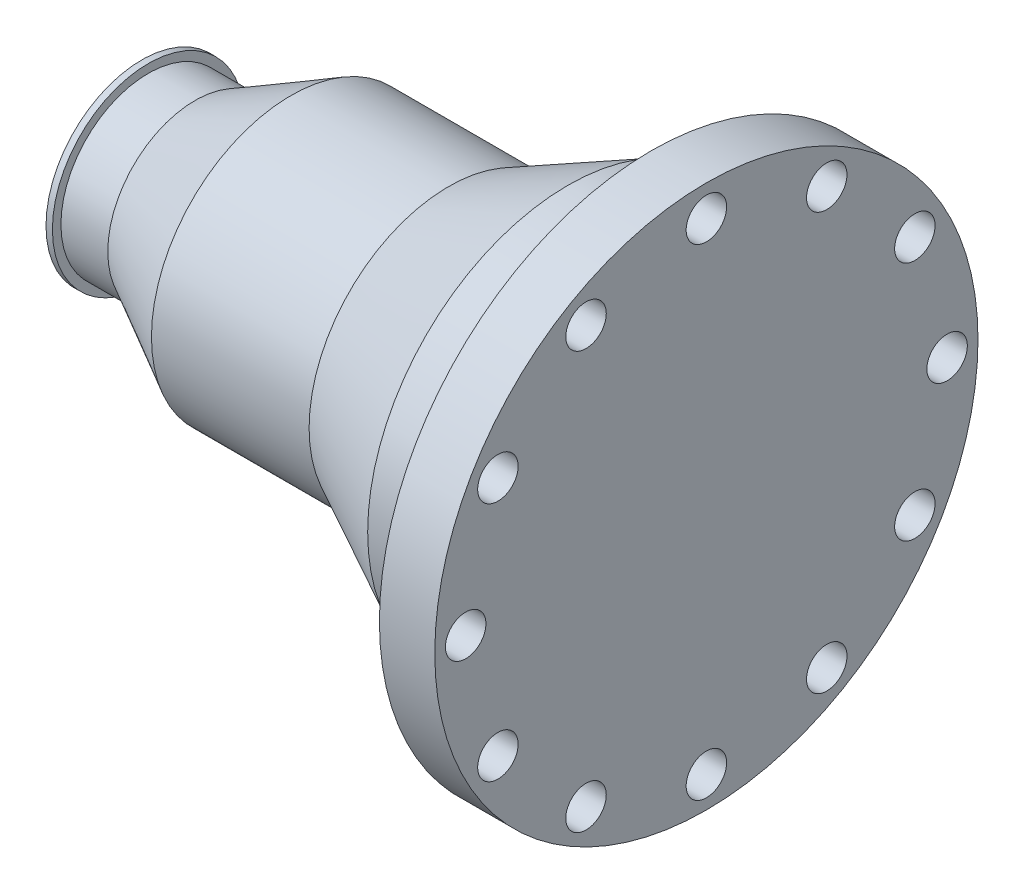
SolidWorks part; units mm, degrees
ref_plane "Спереди" through (0, 0, 0) normal (0, 0, 1) x (1, 0, 0)
ref_plane "Сверху" through (0, 0, 0) normal (0, 1, 0) x (1, 0, 0)
ref_plane "Справа" through (0, 0, 0) normal (1, 0, 0) x (0, 0, -1)
sketch "Эскиз1" plane through (0, 0, 0) normal (0, 0, 1) x (1, 0, 0)
  line L0 (0, 0) -> (265, 0)
  line L1 (0, 0) -> (0, 45)
  line L2 (0, 45) -> (3, 45)
  line L3 (3, 45) -> (3, 41)
  line L4 (3, 41) -> (25, 41)
  line L5 (25, 41) -> (70, 65.5)
  line L6 (70, 65.5) -> (144, 65.5)
  line L7 (144, 65.5) -> (200, 94)
  line L8 (200, 94) -> (220, 94)
  line L9 (220, 94) -> (220, 95)
  line L10 (220, 95) -> (239, 95)
  line L11 (239, 95) -> (239, 100)
  line L12 (239, 100) -> (239, 127.5)
  line L13 (239, 127.5) -> (265, 127.5)
  line L14 (265, 127.5) -> (265, 0)
revolve "Повернуть1" add sketch "Эскиз1" angle 360 about L0
sketch "Эскиз2" plane through (0, 0, 0) normal (1, 0, 0) x (0, 0, -1)
  circle A0 centre (0, 113) radius 9.5
extrude "Вырез-Вытянуть1" cut sketch "Эскиз2" along normal through all
sketch "Эскиз3" plane through (0, 0, 0) normal (1, 0, 0) x (0, 0, -1)
  circle A0 centre (-56.5, 97.8609) radius 9.5
extrude "Вырез-Вытянуть2" cut sketch "Эскиз3" along normal through all
sketch "Эскиз4" plane through (0, 0, 0) normal (1, 0, 0) x (0, 0, -1)
  circle A0 centre (-97.8609, 56.5) radius 9.5
extrude "Вырез-Вытянуть3" cut sketch "Эскиз4" along normal through all
sketch "Эскиз5" plane through (0, 0, 0) normal (1, 0, 0) x (0, 0, -1)
  circle A0 centre (-113, 0) radius 9.5
extrude "Вырез-Вытянуть4" cut sketch "Эскиз5" along normal through all
sketch "Эскиз6" plane through (0, 0, 0) normal (1, 0, 0) x (0, 0, -1)
  circle A0 centre (-97.8609, -56.5) radius 9.5
extrude "Вырез-Вытянуть5" cut sketch "Эскиз6" along normal through all
sketch "Эскиз7" plane through (0, 0, 0) normal (1, 0, 0) x (0, 0, -1)
  circle A0 centre (-56.5, -97.8609) radius 9.5
extrude "Вырез-Вытянуть6" cut sketch "Эскиз7" along normal through all
sketch "Эскиз8" plane through (0, 0, 0) normal (1, 0, 0) x (0, 0, -1)
  circle A0 centre (0, -113) radius 9.5
extrude "Вырез-Вытянуть7" cut sketch "Эскиз8" along normal through all
sketch "Эскиз9" plane through (0, 0, 0) normal (1, 0, 0) x (0, 0, -1)
  circle A0 centre (56.5, -97.8609) radius 9.5
extrude "Вырез-Вытянуть8" cut sketch "Эскиз9" along normal through all
sketch "Эскиз10" plane through (0, 0, 0) normal (1, 0, 0) x (0, 0, -1)
  circle A0 centre (97.8609, -56.5) radius 9.5
extrude "Вырез-Вытянуть9" cut sketch "Эскиз10" along normal through all
sketch "Эскиз11" plane through (0, 0, 0) normal (1, 0, 0) x (0, 0, -1)
  circle A0 centre (113, 0) radius 9.5
extrude "Вырез-Вытянуть10" cut sketch "Эскиз11" along normal through all
sketch "Эскиз12" plane through (0, 0, 0) normal (1, 0, 0) x (0, 0, -1)
  circle A0 centre (97.8609, 56.5) radius 9.5
extrude "Вырез-Вытянуть11" cut sketch "Эскиз12" along normal through all
sketch "Эскиз13" plane through (0, 0, 0) normal (1, 0, 0) x (0, 0, -1)
  circle A0 centre (56.5, 97.8609) radius 9.5
extrude "Вырез-Вытянуть12" cut sketch "Эскиз13" along normal through all
